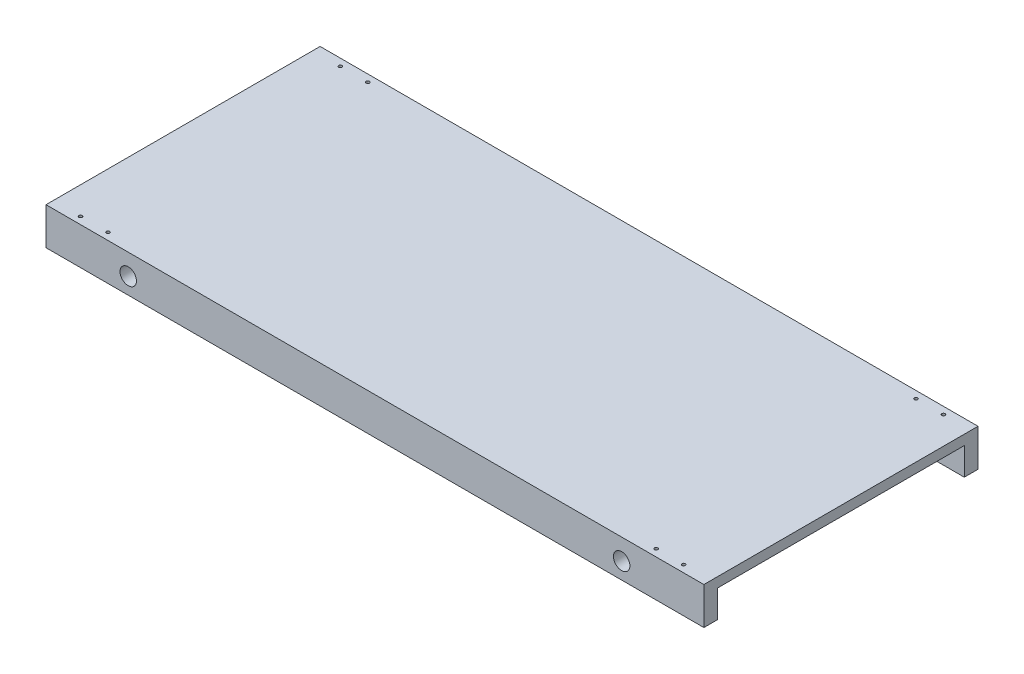
SolidWorks part; units mm, degrees
ref_plane "Front Plane" through (0, 0, 0) normal (0, 0, 1) x (1, 0, 0)
ref_plane "Top Plane" through (0, 0, 0) normal (0, 1, 0) x (1, 0, 0)
ref_plane "Right Plane" through (0, 0, 0) normal (1, 0, 0) x (0, 0, -1)
sketch "Sketch1" plane through (0, 0, 0) normal (0, 1, 0) x (1, 0, 0)
  line L1 (0, 0) -> (1200, 0)
  line L2 (0, 0) -> (0, 500)
  line L3 (0, 500) -> (1200, 500)
  line L4 (1200, 0) -> (1200, 500)
  dimension "D1" = 1200
  dimension "D2" = 500
extrude "Boss-Extrude1" add sketch "Sketch1" along normal blind 68
sketch "Sketch3" plane through (0, 0, 0) normal (0, 0, 1) x (1, 0, 0)
  line L0 (0, 68) -> (0, 0) construction
  line L1 (0, 0) -> (1200, 0) construction
  circle A0 centre (150, 30) radius 15
  dimension "D1" = 30
  dimension "D2" = 150
  dimension "D3" = 30
extrude "Cut-Extrude2" cut sketch "Sketch3" against normal through all
sketch "Sketch4" plane through (0, 0, -500) normal (0, 0, -1) x (-1, 0, 0)
  line L0 (-1200, 68) -> (-1200, 0) construction
  line L1 (-1200, 0) -> (0, 0) construction
  circle A0 centre (-1050, 30) radius 15
  point P4 (-1200, 34)
  dimension "D1" = 30
  dimension "D2" = 150
  dimension "D3" = 30
extrude "Cut-Extrude3" cut sketch "Sketch4" against normal through all
sketch "Sketch2" plane through (0, 0, 0) normal (0, -1, 0) x (1, 0, 0)
  line L0 (0, 0) -> (1200, 0) construction
  line L1 (0, -25) -> (1200, -25)
  line L2 (0, -25) -> (0, -475)
  line L3 (0, -475) -> (1200, -475)
  line L4 (1200, -25) -> (1200, -475)
  line L5 (0, -500) -> (0, 0) construction
  dimension "D1" = 1200
  dimension "D2" = 450
  dimension "D3" = 25
  dimension "D4" = 0
extrude "Cut-Extrude1" cut sketch "Sketch2" against normal blind 50
hole_wizard "Ø6.0 (6) Diameter Hole1" positions "Sketch5" profile "Sketch6" hole size "Ø6.0" standard "ISO" end condition through all
sketch "Sketch5" plane through (0, 68, 0) normal (0, 1, 0) x (1, 0, 0)
  line L0 (0, 500) -> (0, 0) construction
  line L1 (1200, 500) -> (0, 500) construction
  point P0 (50, 487)
  dimension "D1" = 50
  dimension "D2" = 13
sketch "Sketch6" plane through (50, 68, -487) normal (1, 0, 0) x (0, 0, 1)
  line L0 (0, 0) -> (0, 68)
  line L1 (0, 68) -> (3, 68)
  line L2 (3, 68) -> (3, 0)
  line L5 (3, 0) -> (0, 0)
  line L11 (0, -6.35) -> (0, 107.95) construction
  dimension "Thru Hole Dia." = 6
  dimension "Thru Hole Depth" = 68
hole_wizard "Ø6.0 (6) Diameter Hole2" positions "Sketch7" profile "Sketch8" hole size "Ø6.0" standard "ISO" end condition through all
sketch "Sketch7" plane through (0, 68, 0) normal (0, 1, 0) x (1, 0, 0)
  line L0 (1200, 500) -> (0, 500) construction
  line L1 (0, 500) -> (0, 0) construction
  point P0 (100, 487)
  dimension "D1" = 13
  dimension "D2" = 100
sketch "Sketch8" plane through (100, 68, -487) normal (1, 0, 0) x (0, 0, 1)
  line L0 (0, 0) -> (0, 68)
  line L1 (0, 68) -> (3, 68)
  line L2 (3, 68) -> (3, 0)
  line L5 (3, 0) -> (0, 0)
  line L11 (0, -6.35) -> (0, 107.95) construction
  dimension "Thru Hole Dia." = 6
  dimension "Thru Hole Depth" = 68
hole_wizard "Ø6.0 (6) Diameter Hole3" positions "Sketch9" profile "Sketch10" hole size "Ø6.0" standard "ISO" end condition through all
sketch "Sketch9" plane through (0, 68, 0) normal (0, 1, 0) x (1, 0, 0)
  line L0 (1200, 0) -> (1200, 500) construction
  line L1 (0, 0) -> (1200, 0) construction
  line L2 (1200, 500) -> (0, 500) construction
  line L3 (0, 500) -> (0, 0) construction
  point P0 (1150, 487)
  point P2 (1100, 487)
  point P4 (1100, 13)
  point P6 (1150, 13)
  point P8 (50, 13)
  point P10 (100, 13)
  dimension "D1" = 50
  dimension "D2" = 13
  dimension "D3" = 13
  dimension "D4" = 100
  dimension "D5" = 50
  dimension "D6" = 13
  dimension "D7" = 100
  dimension "D8" = 13
  dimension "D9" = 13
  dimension "D10" = 13
  dimension "D11" = 50
  dimension "D12" = 100
sketch "Sketch10" plane through (1150, 68, -487) normal (1, 0, 0) x (0, 0, 1)
  line L0 (0, 0) -> (0, 68)
  line L1 (0, 68) -> (3, 68)
  line L2 (3, 68) -> (3, 0)
  line L5 (3, 0) -> (0, 0)
  line L11 (0, -6.35) -> (0, 107.95) construction
  dimension "Thru Hole Dia." = 6
  dimension "Thru Hole Depth" = 68
